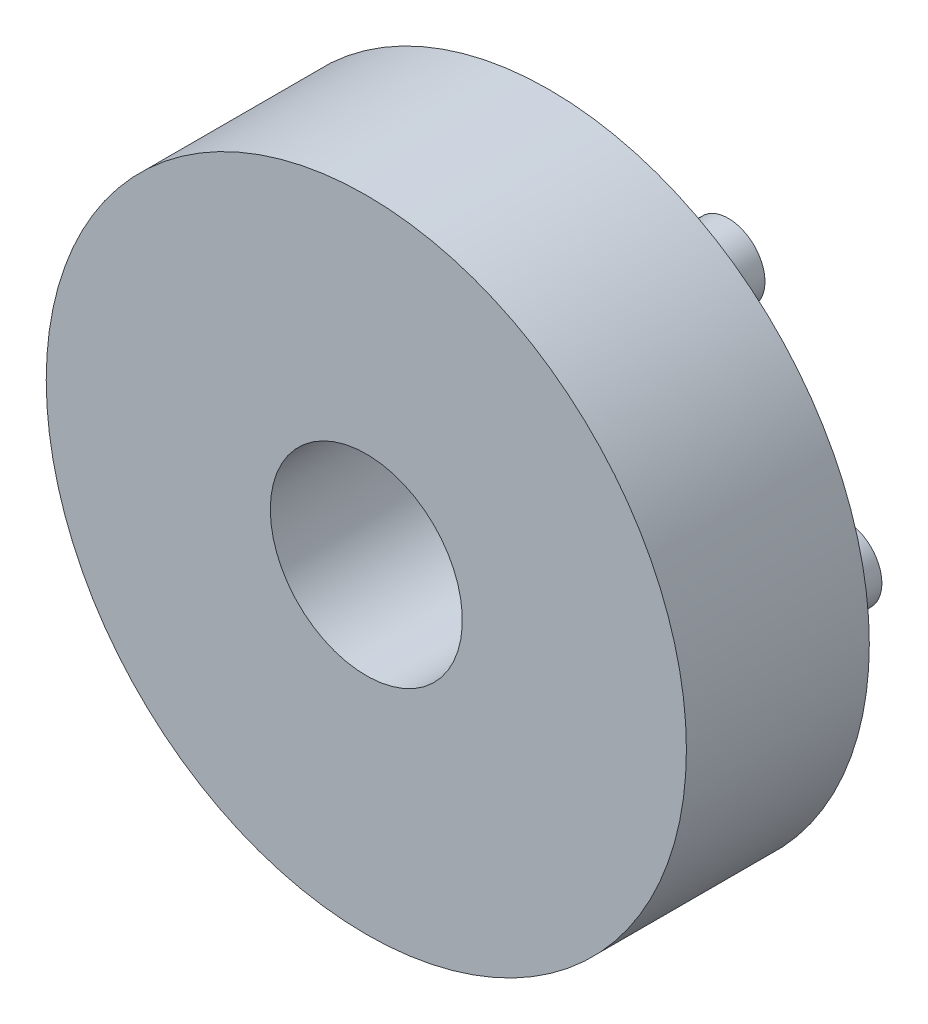
SolidWorks part; units mm, degrees
ref_plane "Plan de face" through (0, 0, 0) normal (0, 0, 1) x (1, 0, 0)
ref_plane "Plan de dessus" through (0, 0, 0) normal (0, 1, 0) x (1, 0, 0)
ref_plane "Plan de droite" through (0, 0, 0) normal (1, 0, 0) x (0, 0, -1)
sketch "Esquisse1" plane through (0, 0, 0) normal (0, 0, 1) x (1, 0, 0)
  circle A0 centre (0, 0) radius 35
  circle A1 centre (0, 0) radius 7
  dimension "D1" = 70
  dimension "D2" = 14
extrude "Boss.-Extru.1" add sketch "Esquisse1" along normal blind 20
sketch "Esquisse2" plane through (0, 0, 0) normal (0, 0, -1) x (-1, 0, 0)
  circle A0 centre (0, 0) radius 14
  dimension "D1" = 28
extrude "Enlèv. mat.-Extru.1" cut sketch "Esquisse2" against normal blind 5
sketch "Esquisse3" plane through (0, 0, 0) normal (0, 0, -1) x (-1, 0, 0)
  line L0 (0, 35) -> (0, -35) construction
  line L1 (-30.3227, 17.4796) -> (30.3227, -17.4796) construction
  line L2 (30.318, 17.4877) -> (-30.318, -17.4877) construction
  circle A0 centre (0, 0) radius 35 construction
  arc A1 (0, 35) -> (-30.3227, 17.4796) centre (0, 0) ccw
  arc A2 (0, 35) -> (30.318, 17.4877) centre (0, 0) cw
  circle A3 centre (-13.589, 22.6021) radius 4
  circle A4 centre (-26.3691, 0.4318) radius 4
  circle A5 centre (26.3691, 0.4318) radius 4
  circle A6 centre (13.589, 22.6021) radius 4
  circle A7 centre (-12.8293, -23.0418) radius 4
  circle A8 centre (12.8416, -23.035) radius 4
  dimension "D1" = 8
extrude "Enlèv. mat.-Extru.3" cut sketch "Esquisse3" against normal blind 5 contours A3 | A6 | A5 | A8 | A7 | A4
sketch "Esquisse8" plane through (0, 0, 0) normal (0, 0, -1) x (-1, 0, 0)
  circle A0 centre (0, 0) radius 14
  dimension "D1" = 28
extrude "Enlèv. mat.-Extru.4" cut sketch "Esquisse8" against normal blind 25
sketch "Esquisse9" plane through (0, 0, 0) normal (0, 0, -1) x (-1, 0, 0)
  circle A1 centre (-13.589, 22.6021) radius 4
  circle A2 centre (13.589, 22.6021) radius 4
  circle A3 centre (26.3691, 0.4318) radius 4
  circle A4 centre (12.8416, -23.035) radius 4
  circle A5 centre (-12.8293, -23.0418) radius 4
  circle A6 centre (-26.3691, 0.4318) radius 4
extrude "Boss.-Extru.2" add sketch "Esquisse9" along normal blind 6 and the other way blind 9 contours A1 | A2 | A3 | A4 | A5 | A6
sketch "Esquisse10" plane through (0, 0, 0) normal (0, 0, -1) x (-1, 0, 0)
  circle A0 centre (0, 0) radius 14
  circle A1 centre (0, 0) radius 10.5
  dimension "D1" = 21
extrude "Boss.-Extru.3" add sketch "Esquisse10" against normal blind 20
